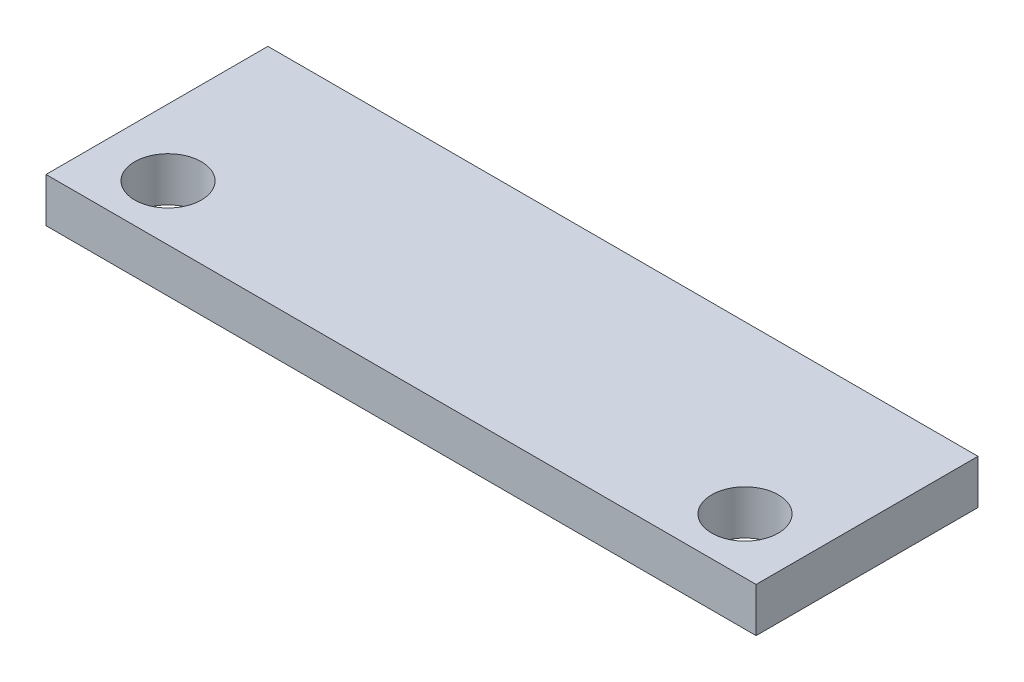
SolidWorks part; units mm, degrees
ref_plane "Front Plane" through (0, 0, 0) normal (0, 0, 1) x (1, 0, 0)
ref_plane "Top Plane" through (0, 0, 0) normal (0, 1, 0) x (1, 0, 0)
ref_plane "Right Plane" through (0, 0, 0) normal (1, 0, 0) x (0, 0, -1)
sketch "Sketch1" plane through (0, 0, 0) normal (0, 1, 0) x (1, 0, 0)
  line L0 (-13, -2.5) -> (13, -2.5) construction
  line L1 (-16, 5) -> (16, 5)
  line L2 (-16, 5) -> (-16, -5)
  line L3 (-16, -5) -> (16, -5)
  line L4 (16, 5) -> (16, -5)
  line L5 (-16, 5) -> (16, -5) construction
  line L6 (-16, -5) -> (16, 5) construction
  circle A0 centre (-13, -2.5) radius 1.5
  circle A1 centre (13, -2.5) radius 1.5
  point P0 (0, 0)
  point P9 (0, -2.5)
  dimension "D5" = 3
  dimension "D1" = 10
  dimension "D2" = 32
  dimension "D3" = 26
  dimension "D4" = 2.5
extrude "Boss-Extrude1" add sketch "Sketch1" along normal blind 2
